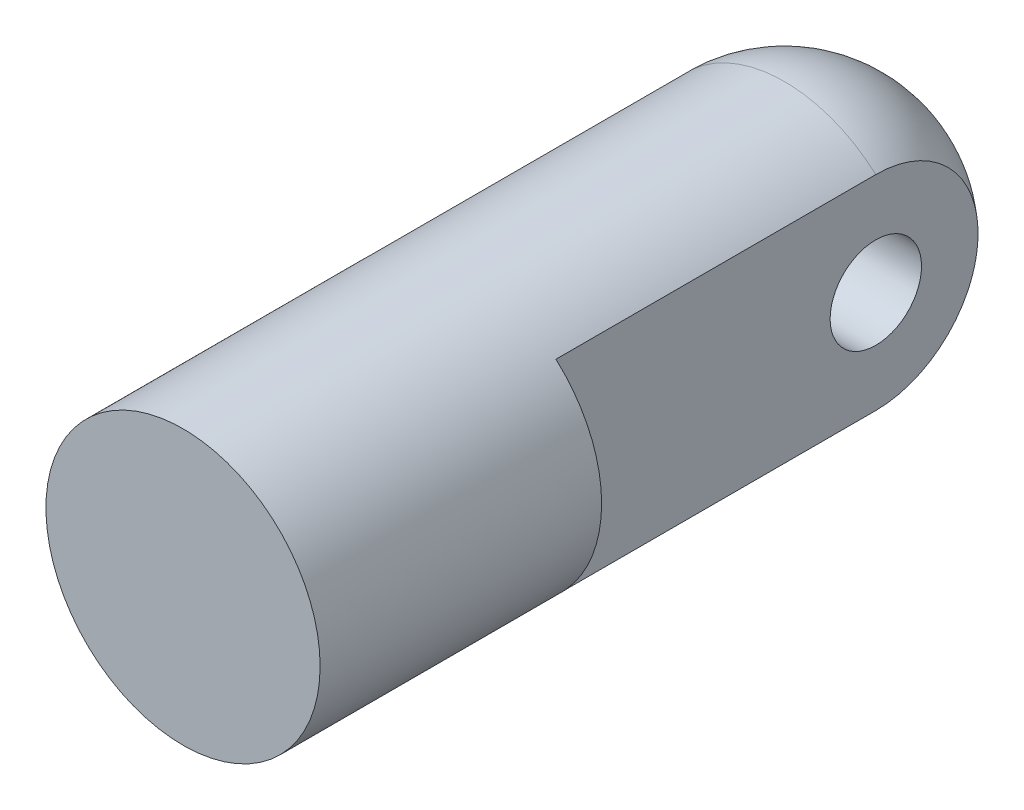
SolidWorks part; units mm, degrees
ref_plane "Front Plane" through (0, 0, 0) normal (0, 0, 1) x (1, 0, 0)
ref_plane "Top Plane" through (0, 0, 0) normal (0, 1, 0) x (1, 0, 0)
ref_plane "Right Plane" through (0, 0, 0) normal (1, 0, 0) x (0, 0, -1)
sketch "Sketch1" plane through (0, 0, 0) normal (0, 1, 0) x (1, 0, 0)
  line L3 (0, 0) -> (0, 28.575)
  line L4 (0, 0) -> (9.525, 0)
  line L5 (9.525, 0) -> (9.525, 28.575)
  line L6 (0, 38.1) -> (0, 28.575)
  arc A3 (9.525, 28.575) -> (0, 38.1) centre (0, 28.575) ccw
  dimension "D1" = 9.525
  dimension "D2" = 38.1
revolve "Revolve1" add sketch "Sketch1" angle 360 about L6
sketch "Sketch2" plane through (0, 0, 0) normal (0, 1, 0) x (1, 0, 0)
  line L0 (-6.35, 66.3542) -> (-6.35, 6.35)
  line L1 (-6.35, 6.35) -> (-19.05, 6.35)
  line L2 (-19.05, 6.35) -> (-19.05, 66.3542)
  line L3 (-19.05, 66.3542) -> (-6.35, 66.3542)
  line L5 (-9.525, 0) -> (9.525, 0) construction
  dimension "D1" = 12.7
  dimension "D2" = 6.35
  dimension "D3" = 6.35
extrude "Cut-Extrude1" cut sketch "Sketch2" against normal through all and the other way through all
mirror "Mirror1" about plane through (0, 0, 0) normal (1, 0, 0) of "Cut-Extrude1"
sketch "Sketch3" plane through (-6.35, 0, 0) normal (-1, 0, 0) x (0, 0, 1)
  circle A0 centre (-28.575, 0) radius 3.175
  arc A1 (-28.575, 7.0995) -> (-28.575, -7.0995) centre (-28.575, 0) ccw construction
  dimension "D1" = 6.35
extrude "Cut-Extrude2" cut sketch "Sketch3" against normal through all
sketch "Sketch11" plane through (0, 0, 0) normal (0, 0, 1) x (1, 0, 0)
  circle A0 centre (0, 0) radius 9.525
extrude "Boss-Extrude2" add sketch "Sketch11" along normal blind 13.208
